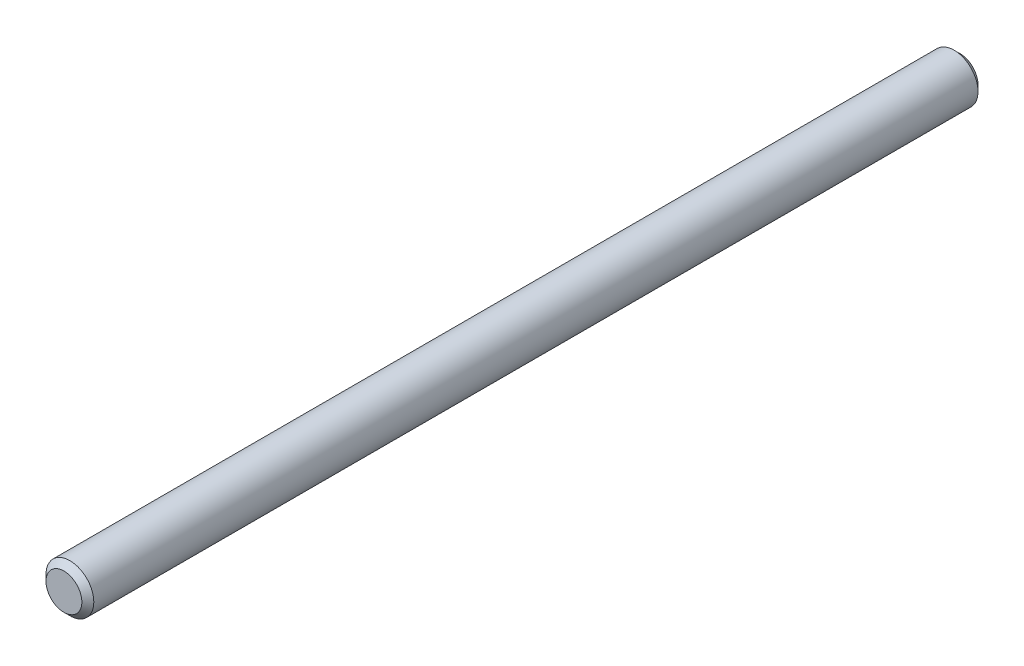
SolidWorks part; units mm, degrees
ref_plane "Front Plane" through (0, 0, 0) normal (0, 0, 1) x (1, 0, 0)
ref_plane "Top Plane" through (0, 0, 0) normal (0, 1, 0) x (1, 0, 0)
ref_plane "Right Plane" through (0, 0, 0) normal (1, 0, 0) x (0, 0, -1)
sketch "Sketch1" plane through (0, 0, 0) normal (0, 0, 1) x (1, 0, 0)
  circle A0 centre (0, 0) radius 4
  dimension "D1" = 8
extrude "Boss-Extrude1" add sketch "Sketch1" along normal blind 150
chamfer "Chamfer1" distance 1 angle 45 2 edges at (4, 0, 150) (4, 0, 0)
